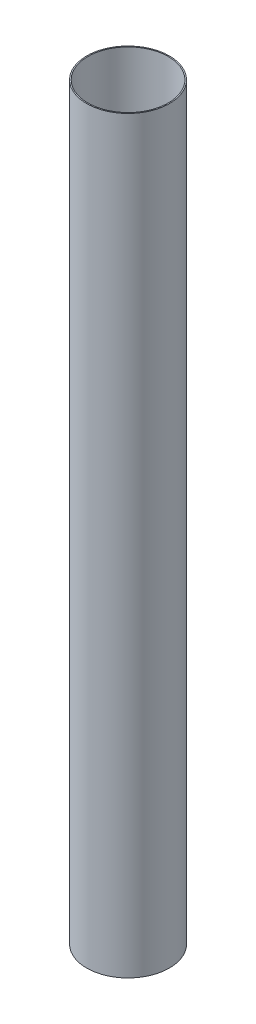
SolidWorks part; units mm, degrees
material "Wildman Fiberglass"
ref_plane "Front Plane" through (0, 0, 0) normal (0, 0, 1) x (1, 0, 0)
ref_plane "Top Plane" through (0, 0, 0) normal (0, 1, 0) x (1, 0, 0)
ref_plane "Right Plane" through (0, 0, 0) normal (1, 0, 0) x (0, 0, -1)
sketch "Sketch1" plane through (0, 0, 0) normal (0, 1, 0) x (1, 0, 0)
  circle A0 centre (0, 0) radius 68.2625
  circle A1 centre (0, 0) radius 70.1675
  dimension "D1" = 140.335
  dimension "D2" = 136.525
extrude "Boss-Extrude1" add sketch "Sketch1" along normal blind 1270
equation "\"Length\"= 50"
equation "\"D1@Boss-Extrude1\"=\"Length\""
